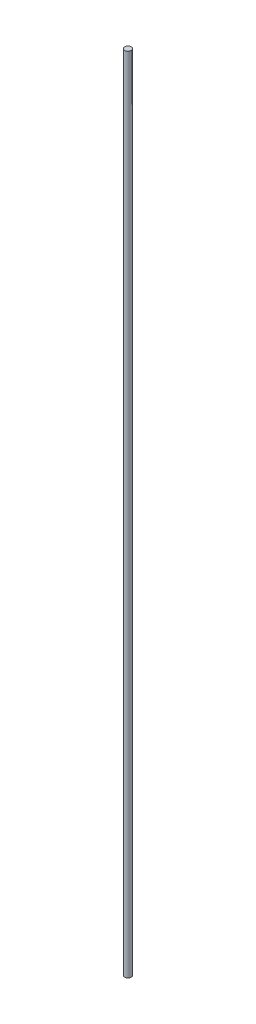
SolidWorks part; units mm, degrees
ref_plane "Front Plane" through (0, 0, 0) normal (0, 0, 1) x (1, 0, 0)
ref_plane "Top Plane" through (0, 0, 0) normal (0, 1, 0) x (1, 0, 0)
ref_plane "Right Plane" through (0, 0, 0) normal (1, 0, 0) x (0, 0, -1)
sketch "Sketch1" plane through (0, 0, 0) normal (0, 1, 0) x (1, 0, 0)
  circle A0 centre (0, 0) radius 3.175
  dimension "D1" = 6.35
extrude "Boss-Extrude1" add sketch "Sketch1" along normal blind 787.4 contours A0
